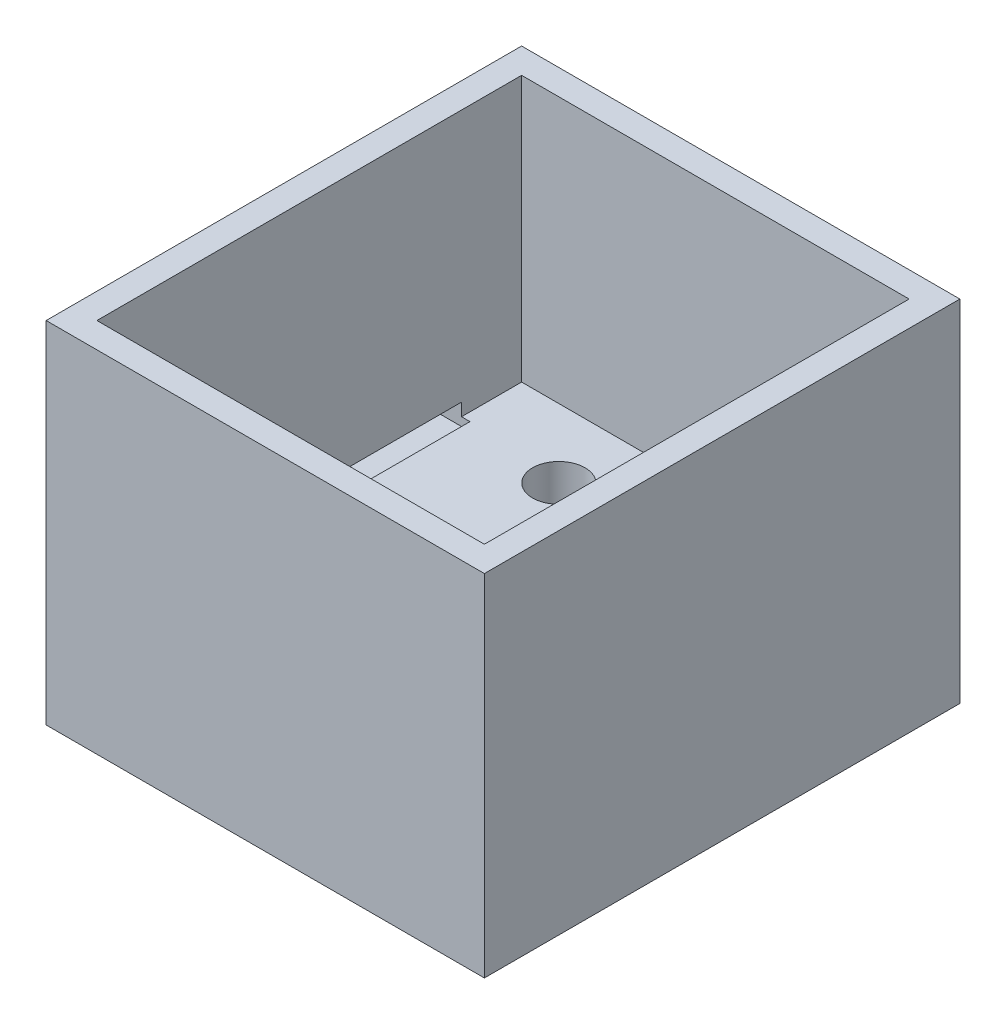
SolidWorks part; units mm, degrees
ref_plane "Front Plane" through (0, 0, 0) normal (0, 0, 1) x (1, 0, 0)
ref_plane "Top Plane" through (0, 0, 0) normal (0, 1, 0) x (1, 0, 0)
ref_plane "Right Plane" through (0, 0, 0) normal (1, 0, 0) x (0, 0, -1)
sketch "Sketch1" plane through (0, 0, 0) normal (0, 1, 0) x (1, 0, 0)
  line L18 (0, 25.1) -> (-3, 25.1)
  line L19 (-3, 25.1) -> (-3, -3)
  line L20 (-3, -3) -> (22.9, -3)
  line L21 (22.9, -3) -> (22.9, 25.1)
  line L22 (22.9, 25.1) -> (0, 25.1)
  circle A2 centre (17.36, 2.54) radius 1.55
  circle A3 centre (4.76, 19.54) radius 1.55
extrude "Boss-Extrude1" add sketch "Sketch1" along normal blind 5
sketch "Sketch2" plane through (0, 5, 0) normal (0, 1, 0) x (1, 0, 0)
  line L0 (-3, 25.1) -> (-3, -3)
  line L2 (-3, -3) -> (22.9, -3)
  line L3 (22.9, -3) -> (22.9, 25.1)
  line L5 (22.9, 25.1) -> (-3, 25.1)
  line L10 (-1.5, 23.6) -> (21.4, 23.6)
  line L11 (21.4, 23.6) -> (21.4, -1.5)
  line L12 (21.4, -1.5) -> (-1.5, -1.5)
  line L13 (-1.5, -1.5) -> (-1.5, 23.6)
extrude "Boss-Extrude2" add sketch "Sketch2" along normal blind 15.7
sketch "Sketch3" plane through (-3, 0, 0) normal (-1, 0, 0) x (0, 0, 1)
  line L6 (-11.05, 4.5) -> (-20.05, 4.5)
  line L7 (-20.05, 4.5) -> (-20.05, 5.75)
  line L8 (-11.05, 4.5) -> (-2.05, 4.5)
  line L9 (-20.05, 5.75) -> (-2.05, 5.75)
  line L10 (-2.05, 5.75) -> (-2.05, 4.5)
extrude "Cut-Extrude1" cut sketch "Sketch3" against normal blind 2
